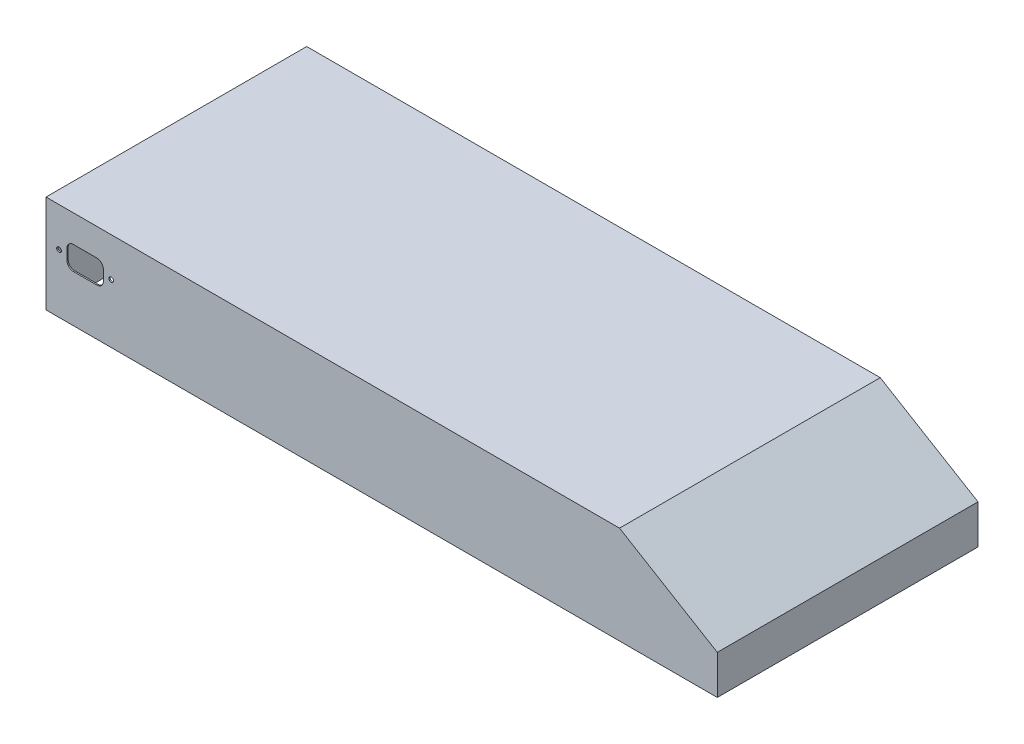
SolidWorks part; units mm, degrees
material "1023 Carbon Steel Sheet (SS)"
ref_plane "Front Plane" through (0, 0, 0) normal (0, 0, 1) x (1, 0, 0)
ref_plane "Top Plane" through (0, 0, 0) normal (0, 1, 0) x (1, 0, 0)
ref_plane "Right Plane" through (0, 0, 0) normal (1, 0, 0) x (0, 0, -1)
sketch "Sketch1" plane through (0, 0, 0) normal (0, 0, 1) x (1, 0, 0)
  line L0 (0, 0) -> (515, 0)
  line L1 (515, 0) -> (515, 30)
  line L2 (515, 30) -> (440, 75)
  line L3 (440, 75) -> (0, 75)
  line L4 (0, 75) -> (0, 0)
  dimension "D1" = 515
  dimension "D2" = 75
  dimension "D3" = 30
  dimension "D4" = 75
extrude "Boss-Extrude1" add sketch "Sketch1" along normal mid plane 200
shell "Shell1" thickness 1
sketch "Sketch2" plane through (0, 0, 100) normal (0, 0, 1) x (1, 0, 0)
  line L0 (440, 75) -> (0, 75) construction
  line L1 (16, 54) -> (44, 54)
  line L2 (16, 54) -> (16, 36)
  line L3 (16, 36) -> (44, 36)
  line L4 (44, 54) -> (44, 36)
  line L5 (0, 75) -> (0, 0) construction
  point P4 (30, 45)
  point P5 (16, 45)
  point P6 (30, 54)
  dimension "D1" = 28
  dimension "D2" = 18
  dimension "D3" = 30
  dimension "D4" = 30
extrude "Cut-Extrude1" cut sketch "Sketch2" against normal up to surface (1 mm away) up to face at (293.9446, 35.4868, 99)
fillet "Fillet1" radius 5 4 edges at (44, 36, 99.5) (44, 54, 99.5) (16, 54, 99.5) (16, 36, 99.5)
hole_wizard "M3 Clearance Hole1" positions "Sketch5" profile "Sketch6" hole size "M3" standard "ANSI Metric"
sketch "Sketch5" plane through (0, 0, 100) normal (0, 0, 1) x (1, 0, 0)
  line L0 (10, 45.0465) -> (50, 45.0465) construction
  line L2 (39, 54) -> (21, 54) construction
  point P0 (10, 45.0465)
  point P2 (50, 45.0465)
  point P9 (30, 45.0465)
  point P12 (30, 54)
  dimension "D1" = 40
sketch "Sketch6" plane through (10, 45.0465, 100) normal (1, 0, 0) x (0, -1, 0)
  line L0 (0, 0) -> (0, 11.0815)
  line L1 (0, 11.0815) -> (1.8, 10)
  line L2 (1.8, 10) -> (1.8, 0)
  line L5 (1.8, 0) -> (0, 0)
  line L10 (0, 11.0815) -> (-1.8, 10) construction
  line L11 (0, -6.35) -> (0, 107.95) construction
  dimension "Hole Dia." = 3.6
  dimension "Hole Depth" = 10
  dimension "Drill Angle" = 118
